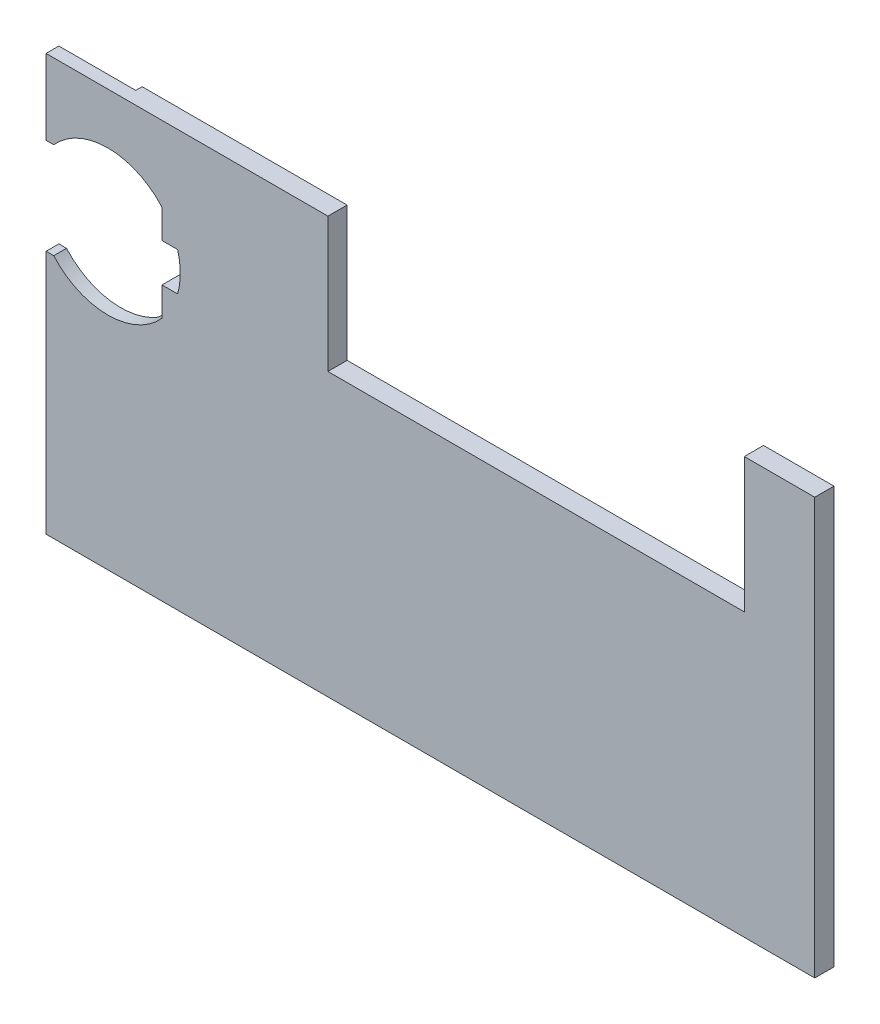
SolidWorks part; units mm, degrees
ref_plane "Přední rovina" through (0, 0, 0) normal (0, 0, 1) x (1, 0, 0)
ref_plane "Horní rovina" through (0, 0, 0) normal (0, 1, 0) x (1, 0, 0)
ref_plane "Pravá rovina" through (0, 0, 0) normal (1, 0, 0) x (0, 0, -1)
sketch "Skica2" plane through (0, 0, 0) normal (0, 0, 1) x (1, 0, 0)
  line L0 (-39.6595, 13.25) -> (1943.3131, 13.25) construction
  line L1 (0, -39.6595) -> (0, 1943.3131) construction
  line L2 (-60, 20.75) -> (-58.8, 20.75)
  line L3 (-41.8956, 20.75) -> (-41.8956, 16.25)
  line L4 (-41.8956, 10.25) -> (-41.8956, 5.75)
  line L5 (-58.8, 5.75) -> (-60, 5.75)
  line L6 (-39.0478, 27.45) -> (-39.0478, 10.25) construction
  line L7 (-60, 32.5) -> (60, 32.5)
  line L8 (-60, 32.5) -> (-60, -32.5) construction
  line L9 (-60, -32.5) -> (60, -32.5)
  line L10 (60, 32.5) -> (60, -32.5) construction
  line L11 (-60, 32.5) -> (60, -32.5) construction
  line L12 (-60, -32.5) -> (60, 32.5) construction
  line L27 (-60, 20.75) -> (-60, 32.5)
  line L28 (-60, 5.75) -> (-60, -32.5)
  line L47 (-41.8956, 16.25) -> (-39.4533, 16.25)
  line L48 (-41.8956, 10.25) -> (-39.4533, 10.25)
  line L51 (60, 32.5) -> (60, -32.5)
  arc A0 (-41.8956, 20.75) -> (-58.8, 20.75) centre (-50.3478, 13.25) ccw
  arc A2 (-58.8, 5.75) -> (-41.8956, 5.75) centre (-50.3478, 13.25) ccw
  circle A3 centre (-50.3478, 13.25) radius 11.3 construction
  arc A19 (-39.4533, 16.25) -> (-39.4533, 10.25) centre (-50.3478, 13.25) cw
  point P15 (-33.7978, 13.25)
  point P16 (0, 0)
  point P26 (0, 0)
  dimension "D1" = 22.6
  dimension "D2" = 6
  dimension "D3" = 15
  dimension "D4" = 1.2
  dimension "D5" = 120
  dimension "D6" = 65
  dimension "D13" = 19.25
extrude "Přidat vysunutím1" add sketch "Skica2" along normal blind 3 contours L7 L51 L9 L28 L5 A2 L4 L48 A19 L47 L3 A0 L2 L27
sketch "Skica3" plane through (0, 0, 0) normal (0, 0, -1) x (-1, 0, 0)
  line L1 (23, 31.5) -> (43.45, 31.5)
  line L2 (23, 31.5) -> (23, 28.5)
  line L3 (23, 28.5) -> (43.45, 28.5)
  line L4 (43.45, 31.5) -> (43.45, 28.5)
  line L5 (23, 31.5) -> (43.45, 28.5) construction
  line L6 (23, 28.5) -> (43.45, 31.5) construction
  line L7 (60, 32.5) -> (-60, 32.5) construction
  line L8 (-60, 32.5) -> (-60, -32.5) construction
  point P0 (33.225, 30)
  dimension "D1" = 20.45
  dimension "D2" = 3
  dimension "D3" = 83
  dimension "D4" = 1
extrude "Odebrat vysunutím1" cut sketch "Skica3" against normal blind 1
sketch "Skica4" plane through (0, 0, 0) normal (0, 0, -1) x (-1, 0, 0)
  line L0 (-59, 31.5) -> (-56, 31.5)
  line L1 (-59, -31.5) -> (43.45, -31.5)
  line L5 (-56, 31.5) -> (-56, -28.5)
  line L6 (-56, -28.5) -> (43.45, -28.5)
  line L8 (43.45, -28.5) -> (43.45, -31.5)
  line L12 (-59, 31.5) -> (-59, -31.5)
  line L13 (-60, 32.5) -> (-60, -32.5) construction
  line L14 (60, -32.5) -> (-60, -32.5) construction
  line L15 (60, 5.75) -> (60, -32.5) construction
  line L16 (60, 32.5) -> (-60, 32.5) construction
  dimension "D1" = 3
  dimension "D2" = 3
  dimension "D3" = 1
  dimension "D4" = 1
  dimension "D5" = 16.55
  dimension "D6" = 1
extrude "Odebrat vysunutím2" cut sketch "Skica4" against normal blind 1
sketch "Skica5" plane through (0, 0, 0) normal (0, 0, -1) x (-1, 0, 0)
  line L1 (60, 32.5) -> (48, 32.5)
  line L2 (60, 32.5) -> (60, -32.5)
  line L3 (60, -32.5) -> (48, -32.5)
  line L4 (44.45, 27.5) -> (44.45, -27.5)
  line L5 (43.45, 28.5) -> (43.45, 31.5) construction
  line L6 (48, 32.5) -> (48, 27.5)
  line L7 (48, 27.5) -> (44.45, 27.5)
  line L8 (44.45, -27.5) -> (48, -27.5)
  line L9 (48, -27.5) -> (48, -32.5)
  line L11 (60, -32.5) -> (-60, -32.5) construction
  point P1 (0, 0)
  point P3 (0, 0)
  point P5 (37.45, -27.513)
  point P6 (0, 0)
  point P14 (42.3145, -32.5)
  dimension "D1" = 1
  dimension "D2" = 5
  dimension "D3" = 90
  dimension "D4" = 5
  dimension "D5" = 12
  dimension "D6" = 12
extrude "Odebrat vysunutím3" cut sketch "Skica5" against normal blind 1
sketch "Skica6" plane through (0, 0, 0) normal (0, 0, -1) x (-1, 0, 0)
  line L0 (48, 32.5) -> (-60, 32.5) construction
  line L1 (-49, 32.5) -> (16, 32.5)
  line L2 (-49, 32.5) -> (-49, 11.5)
  line L3 (-49, 11.5) -> (16, 11.5)
  line L4 (16, 32.5) -> (16, 11.5)
  line L6 (23, 31.5) -> (23, 28.5) construction
  line L7 (-56, -28.5) -> (-56, 31.5) construction
  dimension "D1" = 7
  dimension "D2" = 21
  dimension "D4" = 7
extrude "Odebrat vysunutím4" cut sketch "Skica6" against normal through all
